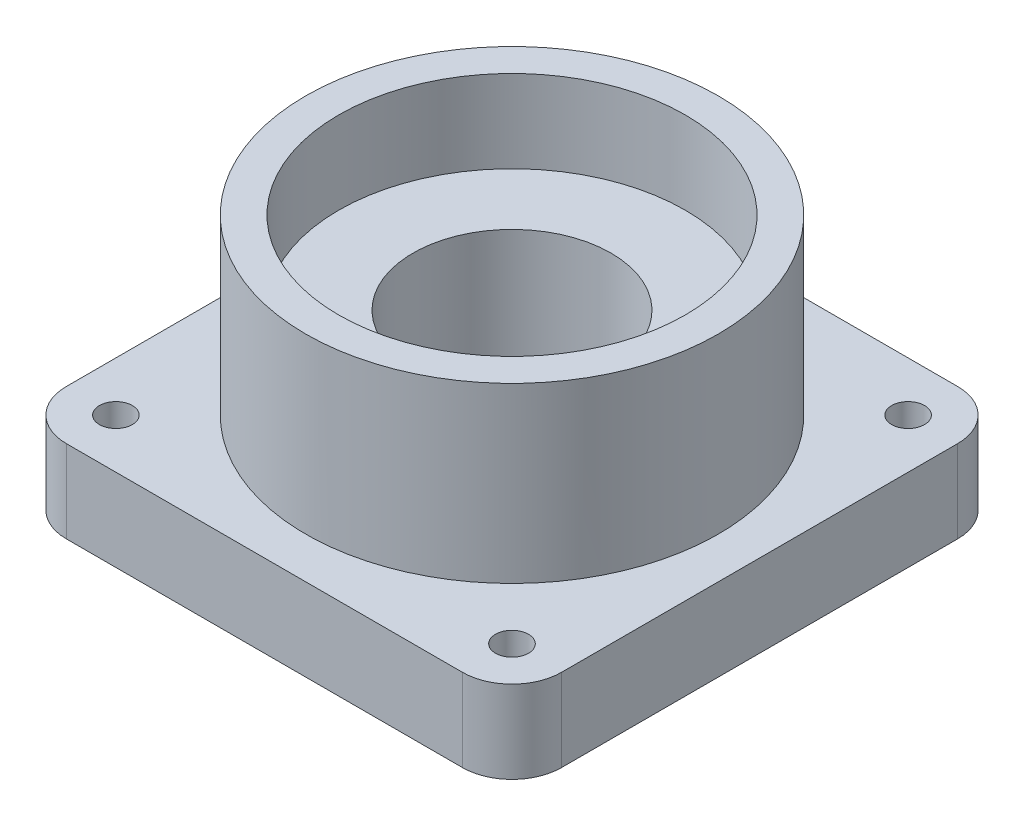
SolidWorks part; units mm, degrees
ref_plane "前视基准面" through (0, 0, 0) normal (0, 0, 1) x (1, 0, 0)
ref_plane "上视基准面" through (0, 0, 0) normal (0, 1, 0) x (1, 0, 0)
ref_plane "右视基准面" through (0, 0, 0) normal (1, 0, 0) x (0, 0, -1)
other "Configuration Table"
sketch "Sketch1" plane through (0, 0, 0) normal (0, 1, 0) x (1, 0, 0)
  line L1 (-15, -15) -> (15, -15)
  line L2 (-15, -15) -> (-15, 15)
  line L3 (-15, 15) -> (15, 15)
  line L4 (15, -15) -> (15, 15)
  line L5 (-15, -15) -> (15, 15) construction
  line L6 (-15, 15) -> (15, -15) construction
  point P0 (0, 0)
extrude "Boss-Extrude1" add sketch "Sketch1" along normal blind 5
sketch "Sketch2" plane through (0, 5, 0) normal (0, 1, 0) x (1, 0, 0)
  line L0 (-15, 15) -> (-15, -15) construction
  line L1 (15, 15) -> (-15, 15) construction
  line L2 (15, -15) -> (15, 15) construction
  line L3 (-15, -15) -> (15, -15) construction
  circle A0 centre (-12, 12) radius 1
  circle A1 centre (12, 12) radius 1
  circle A2 centre (-12, -12) radius 1
  circle A3 centre (12, -12) radius 1
  dimension "D1" = 3
  dimension "D3" = 3
  dimension "D4" = 3
  dimension "D2" = 3
extrude "Cut-Extrude1" cut sketch "Sketch2" against normal up to next
fillet "Fillet1" radius 3 4 edges at (-15, 2.5, -15) (15, 2.5, -15) (15, 2.5, 15) (-15, 2.5, 15)
sketch "Sketch3" plane through (0, 5, 0) normal (0, 1, 0) x (1, 0, 0)
  circle A0 centre (0, 0) radius 12.5
extrude "Boss-Extrude2" add sketch "Sketch3" along normal blind 5.5
sketch "Sketch4" plane through (0, 10.5, 0) normal (0, 1, 0) x (1, 0, 0)
  circle A0 centre (0, 0) radius 10.5
  circle A1 centre (0, 0) radius 12.5
extrude "Boss-Extrude3" add sketch "Sketch4" along normal blind 5
sketch "Sketch5" plane through (0, 10.5, 0) normal (0, 1, 0) x (1, 0, 0)
  circle A0 centre (0, 0) radius 6
extrude "Cut-Extrude2" cut sketch "Sketch5" against normal up to next
